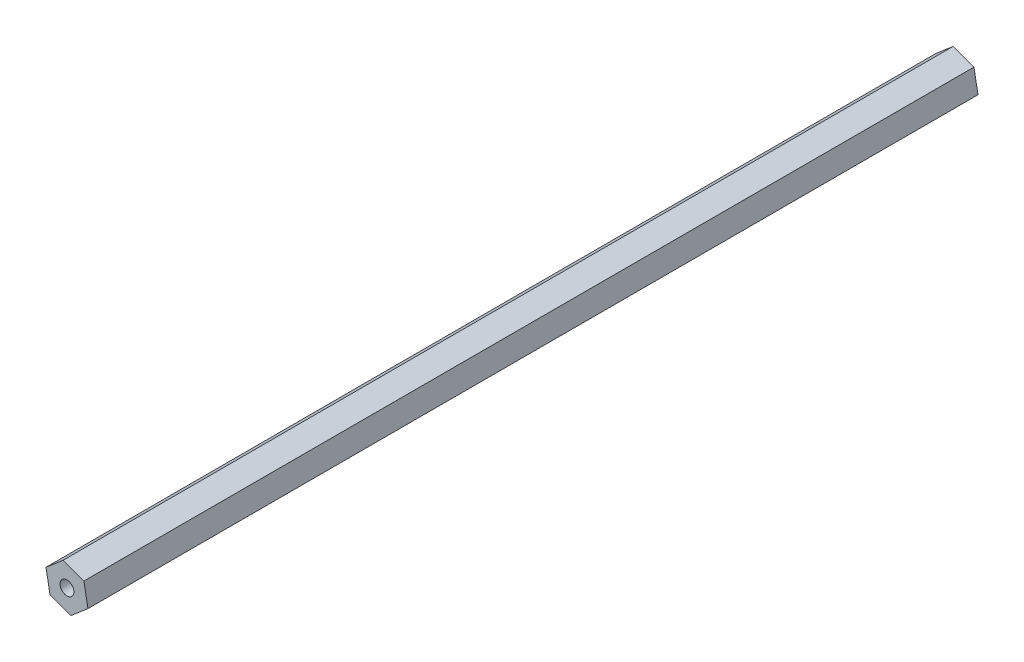
SolidWorks part; units mm, degrees
ref_plane "Front Plane" through (0, 0, 0) normal (0, 0, 1) x (1, 0, 0)
ref_plane "Top Plane" through (0, 0, 0) normal (0, 1, 0) x (1, 0, 0)
ref_plane "Right Plane" through (0, 0, 0) normal (1, 0, 0) x (0, 0, -1)
sketch "Sketch1" plane through (0, 0, 0) normal (0, 0, 1) x (1, 0, 0)
  line L1 (3.7707, -1.3349) -> (3.0414, 2.5981)
  line L2 (3.0414, 2.5981) -> (-0.7293, 3.933)
  line L3 (-0.7293, 3.933) -> (-3.7707, 1.3349)
  line L4 (-3.7707, 1.3349) -> (-3.0414, -2.5981)
  line L5 (-3.0414, -2.5981) -> (0.7293, -3.933)
  line L6 (0.7293, -3.933) -> (3.7707, -1.3349)
  circle A0 centre (0, 0) radius 4 construction
  circle A1 centre (0, 0) radius 3.4641 construction
  dimension "D1" = 8
  dimension "D2" = 2.5981
  dimension "D3" = 4
extrude "Boss-Extrude1" add sketch "Sketch1" along normal blind 160
sketch "Sketch4" plane through (0, 0, 0) normal (0, 0, -1) x (-1, 0, 0)
  circle A0 centre (0, 0) radius 1.25
  dimension "D1" = 2.5
extrude "Cut-Extrude1" cut sketch "Sketch4" against normal blind 5
ref_plane "Plane1" through (0, 0, 80) normal (0, 0, 1) x (1, 0, 0)
mirror "Mirror1" about plane through (0, 0, 80) normal (0, 0, 1) of "Cut-Extrude1"
